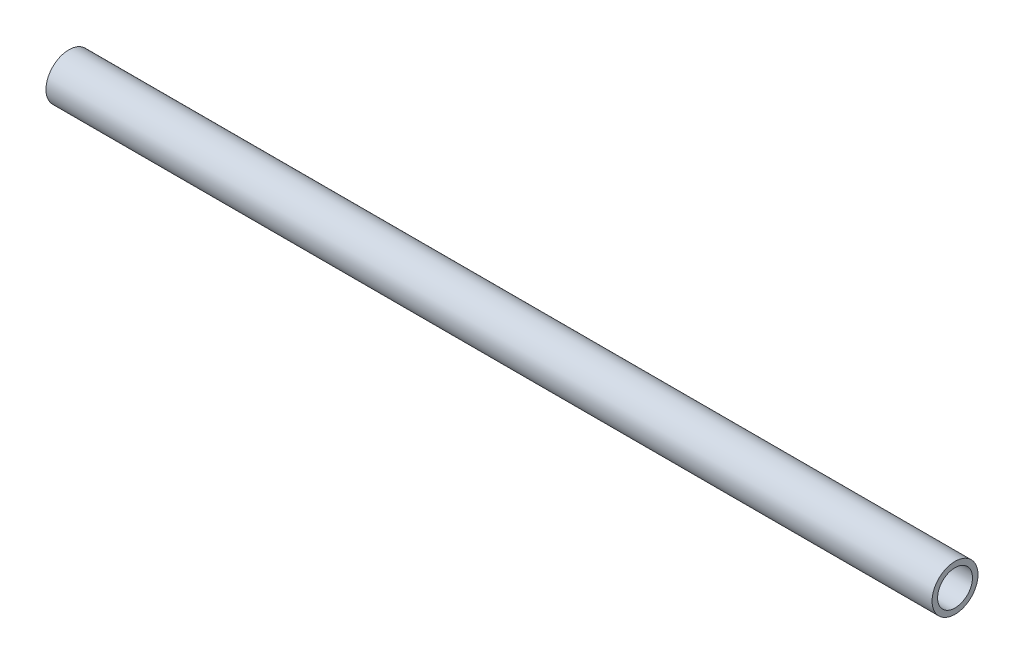
SolidWorks part; units mm, degrees
material "AISI 4130 Steel, annealed at 865C"
ref_plane "Front Plane" through (0, 0, 0) normal (0, 0, 1) x (1, 0, 0)
ref_plane "Top Plane" through (0, 0, 0) normal (0, 1, 0) x (1, 0, 0)
ref_plane "Right Plane" through (0, 0, 0) normal (1, 0, 0) x (0, 0, -1)
sketch "Sketch1" plane through (0, 0, 0) normal (1, 0, 0) x (0, 0, -1)
  circle A0 centre (0, 0) radius 12.7
  circle A1 centre (0, 0) radius 9.652
  dimension "D1" = 25.4
  dimension "D2" = 19.304
extrude "Boss-Extrude1" add sketch "Sketch1" along normal blind 490
